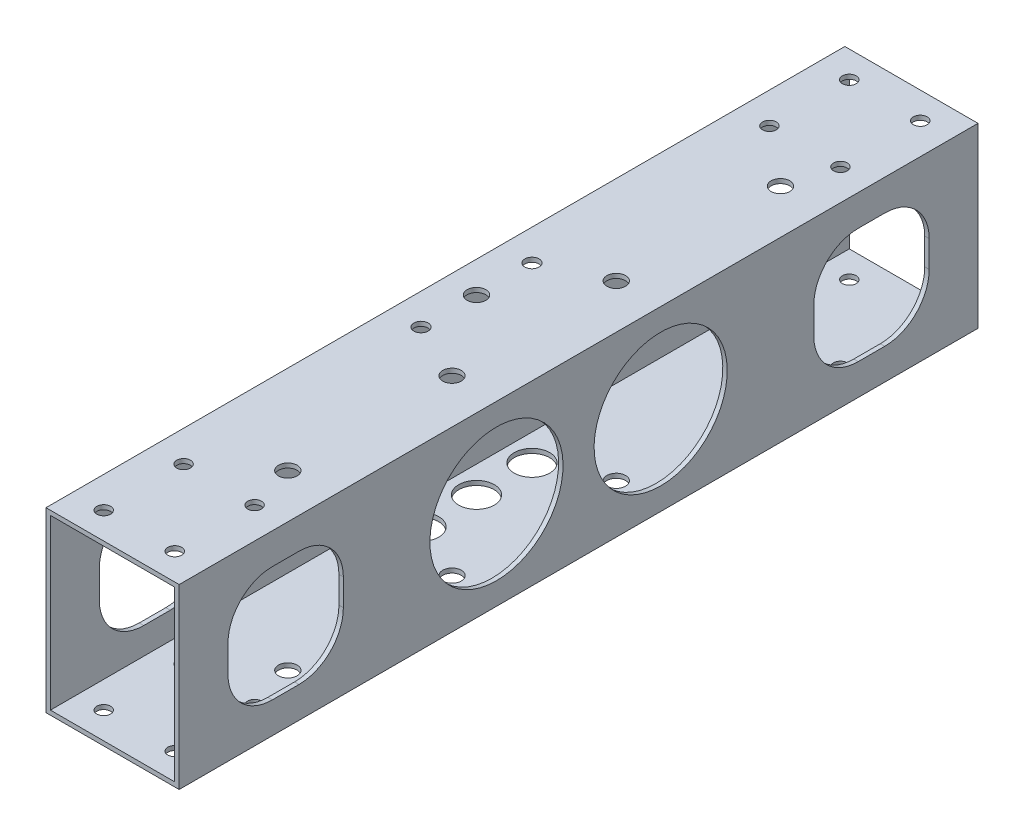
SolidWorks part; units mm, degrees
material "6061 合金"
ref_plane "前视基准面" through (0, 0, 0) normal (0, 0, 1) x (1, 0, 0)
ref_plane "上视基准面" through (0, 0, 0) normal (0, 1, 0) x (1, 0, 0)
ref_plane "右视基准面" through (0, 0, 0) normal (1, 0, 0) x (0, 0, -1)
other "Configuration Table"
sketch "草图1" plane through (0, 0, 0) normal (0, 0, 1) x (1, 0, 0)
  line L1 (-15, 20) -> (15, 20)
  line L2 (-15, 20) -> (-15, -20)
  line L3 (-15, -20) -> (15, -20)
  line L4 (15, 20) -> (15, -20)
  line L5 (-15, 20) -> (15, -20) construction
  line L6 (-15, -20) -> (15, 20) construction
  line L7 (-14, 19) -> (14, 19)
  line L8 (-14, 19) -> (-14, -19)
  line L9 (-14, -19) -> (14, -19)
  line L10 (14, 19) -> (14, -19)
  line L11 (-14, 19) -> (14, -19) construction
  line L12 (-14, -19) -> (14, 19) construction
  point P0 (0, 0)
  point P6 (0, 0)
  dimension "D1" = 30
  dimension "D2" = 40
  dimension "D3" = 1
  dimension "D4" = 1
extrude "凸台-拉伸1" add sketch "草图1" along normal mid plane 180
sketch "草图2" plane through (0, 20, 0) normal (0, 1, 0) x (1, 0, 0)
  line L0 (15, -90) -> (-15, -90) construction
  line L1 (-8, -66) -> (8, -66) construction
  line L2 (-8, -66) -> (-8, -84) construction
  line L3 (-8, -84) -> (8, -84) construction
  line L4 (8, -66) -> (8, -84) construction
  line L5 (-8, -66) -> (8, -84) construction
  line L6 (-8, -84) -> (8, -66) construction
  line L7 (-15, -90) -> (-15, 90) construction
  line L8 (-31.6494, 0) -> (34.7093, 0) construction
  line L9 (-8, 84) -> (8, 66) construction
  line L10 (-8, 66) -> (8, 84) construction
  line L11 (8, 66) -> (8, 84) construction
  line L12 (-8, 84) -> (8, 84) construction
  line L13 (-8, 66) -> (-8, 84) construction
  line L14 (-8, 66) -> (8, 66) construction
  circle A0 centre (-8, -84) radius 1.55
  circle A1 centre (8, -84) radius 1.55
  circle A2 centre (8, -66) radius 1.55
  circle A3 centre (-8, -66) radius 1.55
  circle A4 centre (-8, 66) radius 1.55
  circle A5 centre (8, 66) radius 1.55
  circle A6 centre (8, 84) radius 1.55
  circle A7 centre (-8, 84) radius 1.55
  point P0 (0, -75)
  point P24 (0, 75)
  dimension "D4" = 3.1
  dimension "D1" = 6
  dimension "D2" = 24
  dimension "D3" = 7
extrude "切除-拉伸1" cut sketch "草图2" against normal mid plane 80
sketch "草图3" plane through (0, -19, 0) normal (0, 1, 0) x (1, 0, 0)
  circle A0 centre (5, -55.51) radius 2.1
  circle A1 centre (5, -18.51) radius 2.1
  circle A2 centre (5, 18.49) radius 2.1
  circle A3 centre (5, 55.49) radius 2.1
  dimension "D1" = 4.2
extrude "切除-拉伸2" cut sketch "草图3" against normal blind 10
sketch "草图4" plane through (-15, 0, 0) normal (-1, 0, 0) x (0, 0, 1)
  line L0 (0, -49.2351) -> (0, 29.1162) construction
  line L1 (37, -30.993) -> (37, 29.1162) construction
  line L2 (90, 20) -> (90, -20) construction
  line L3 (63, 13) -> (69, 13)
  line L4 (53, 3) -> (53, -3)
  line L5 (63, -13) -> (69, -13)
  line L6 (79, 3) -> (79, -3)
  line L7 (-63, -13) -> (-69, -13)
  line L8 (-79, 3) -> (-79, -3)
  line L9 (-63, 13) -> (-69, 13)
  line L10 (-53, 3) -> (-53, -3)
  circle A0 centre (18.5, 0) radius 15
  circle A1 centre (-18.5, 0) radius 15
  circle A2 centre (55.5, 0) radius 15 construction
  circle A3 centre (-55.5, 0) radius 15 construction
  arc A4 (53, -3) -> (63, -13) centre (63, -3) ccw
  arc A5 (63, 13) -> (53, 3) centre (63, 3) ccw
  arc A6 (69, 13) -> (79, 3) centre (69, 3) cw
  arc A7 (69, -13) -> (79, -3) centre (69, -3) ccw
  arc A8 (-69, -13) -> (-79, -3) centre (-69, -3) cw
  arc A9 (-69, 13) -> (-79, 3) centre (-69, 3) ccw
  arc A10 (-53, -3) -> (-63, -13) centre (-63, -3) cw
  arc A11 (-63, 13) -> (-53, 3) centre (-63, 3) cw
  point P17 (79, 0)
  point P18 (66, 13)
  point P23 (53, -13)
  point P30 (79, -13)
  dimension "D2" = 30
  dimension "D6" = 10
  dimension "D1" = 18.5
  dimension "D3" = 18.5
  dimension "D4" = 24
  dimension "D5" = 26
extrude "切除-拉伸3" cut sketch "草图4" against normal blind 40
sketch "草图5" plane through (0, 20, 0) normal (0, 1, 0) x (1, 0, 0)
  circle A0 centre (-8, 0) radius 2.1
  circle A1 centre (-8, 12.5) radius 1.6
  circle A2 centre (-8, -12.5) radius 1.6
  dimension "D3" = 3.2
  dimension "D4" = 4.2
  dimension "D1" = 25
  dimension "D2" = 12.5
extrude "切除-拉伸4" cut sketch "草图5" against normal blind 10
sketch "草图6" plane through (0, -19, 0) normal (0, 1, 0) x (1, 0, 0)
  circle A0 centre (-8, -12.5) radius 4
  circle A1 centre (-8, 12.5) radius 4
  circle A2 centre (-8, 0) radius 4
  dimension "D1" = 8
extrude "切除-拉伸5" cut sketch "草图6" against normal blind 10
sketch "草图7" plane through (0, -20, 0) normal (0, -1, 0) x (1, 0, 0)
  circle A0 centre (5, -55.49) radius 2.1 construction
  circle A1 centre (5, -18.49) radius 2.1 construction
  circle A2 centre (5, 18.51) radius 2.1 construction
  circle A3 centre (5, 55.51) radius 2.1 construction
  circle A4 centre (5, -55.49) radius 2.1
  circle A5 centre (5, -18.49) radius 2.1
  circle A6 centre (5, 18.51) radius 2.1
  circle A7 centre (5, 55.51) radius 2.1
extrude "切除-拉伸6" cut sketch "草图7" against normal blind 50
